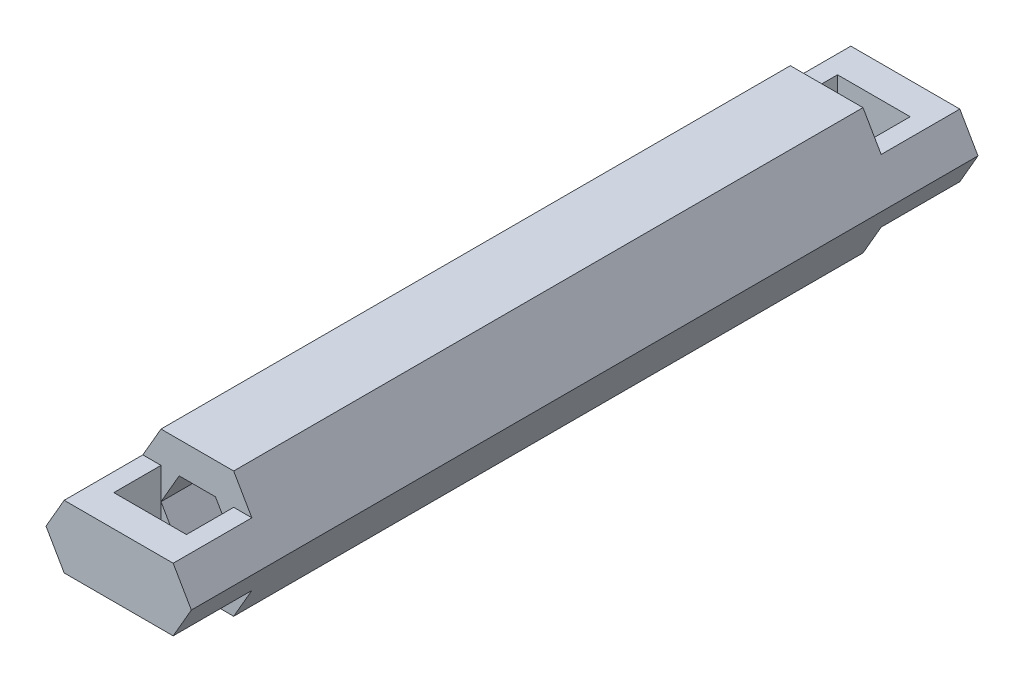
SolidWorks part; units mm, degrees
ref_plane "Front Plane" through (0, 0, 0) normal (0, 0, 1) x (1, 0, 0)
ref_plane "Top Plane" through (0, 0, 0) normal (0, 1, 0) x (1, 0, 0)
ref_plane "Right Plane" through (0, 0, 0) normal (1, 0, 0) x (0, 0, -1)
sketch "Sketch3" plane through (0, 0, 0) normal (0, 0, 1) x (1, 0, 0)
  line L1 (5.7735, 0) -> (2.8868, 5)
  line L2 (2.8868, 5) -> (-2.8868, 5)
  line L3 (-2.8868, 5) -> (-5.7735, 0)
  line L4 (-5.7735, 0) -> (-2.8868, -5)
  line L5 (-2.8868, -5) -> (2.8868, -5)
  line L6 (2.8868, -5) -> (5.7735, 0)
  line L7 (11.547, 0) -> (5.7735, 10)
  line L8 (5.7735, 10) -> (-5.7735, 10)
  line L9 (-5.7735, 10) -> (-11.547, 0)
  line L10 (-11.547, 0) -> (-5.7735, -10)
  line L11 (-5.7735, -10) -> (5.7735, -10)
  line L12 (5.7735, -10) -> (11.547, 0)
  circle A0 centre (0, 0) radius 5 construction
  circle A1 centre (0, 0) radius 10 construction
  dimension "D1" = 10
  dimension "D2" = 20
extrude "Boss-Extrude1" add sketch "Sketch3" along normal blind 100
sketch "Sketch5" plane through (0, 0, 100) normal (0, 0, 1) x (1, 0, 0)
  line L0 (5.7735, 5) -> (8.6603, 5)
  line L1 (11.547, 0) -> (8.6603, 5)
  line L3 (-8.6603, 5) -> (-11.547, 0)
  line L4 (-11.547, 0) -> (-8.6603, -5)
  line L6 (8.6603, -5) -> (11.547, 0)
  line L10 (5.7735, -5) -> (5.7735, 5)
  line L13 (-8.6603, -5) -> (-5.7735, -5)
  line L15 (-8.6603, 5) -> (-5.7735, 5)
  line L21 (5.7735, -5) -> (8.6603, -5)
  line L22 (0, 10) -> (-5.7735, 10) [skipped]
  line L23 (-5.7735, -5) -> (-5.7735, 5)
  line L24 (0, -10) -> (5.7735, -10) [skipped]
  arc A0 (5, -8.6603) -> (5.7735, -8.165) centre (0, 0) ccw construction
extrude "Boss-Extrude2" add sketch "Sketch5" along normal blind 12.5
sketch "Sketch7" plane through (-5.7735, 0, 0) normal (1, 0, 0) x (0, 0, -1)
  line L0 (-112.5, -5) -> (-100, -5) construction
  line L1 (-112.5, 5) -> (-107.5, 5)
  line L2 (-112.5, 5) -> (-112.5, -5)
  line L3 (-112.5, -5) -> (-107.5, -5)
  line L4 (-107.5, 5) -> (-107.5, -5)
  dimension "D1" = 5
extrude "Boss-Extrude3" add sketch "Sketch7" along normal up to next
ref_plane "Plane4" through (0, 0, 50) normal (0, 0, 1) x (1, 0, 0)
mirror "Mirror1" about plane through (0, 0, 50) normal (0, 0, 1) of "Boss-Extrude3", "Boss-Extrude2"
